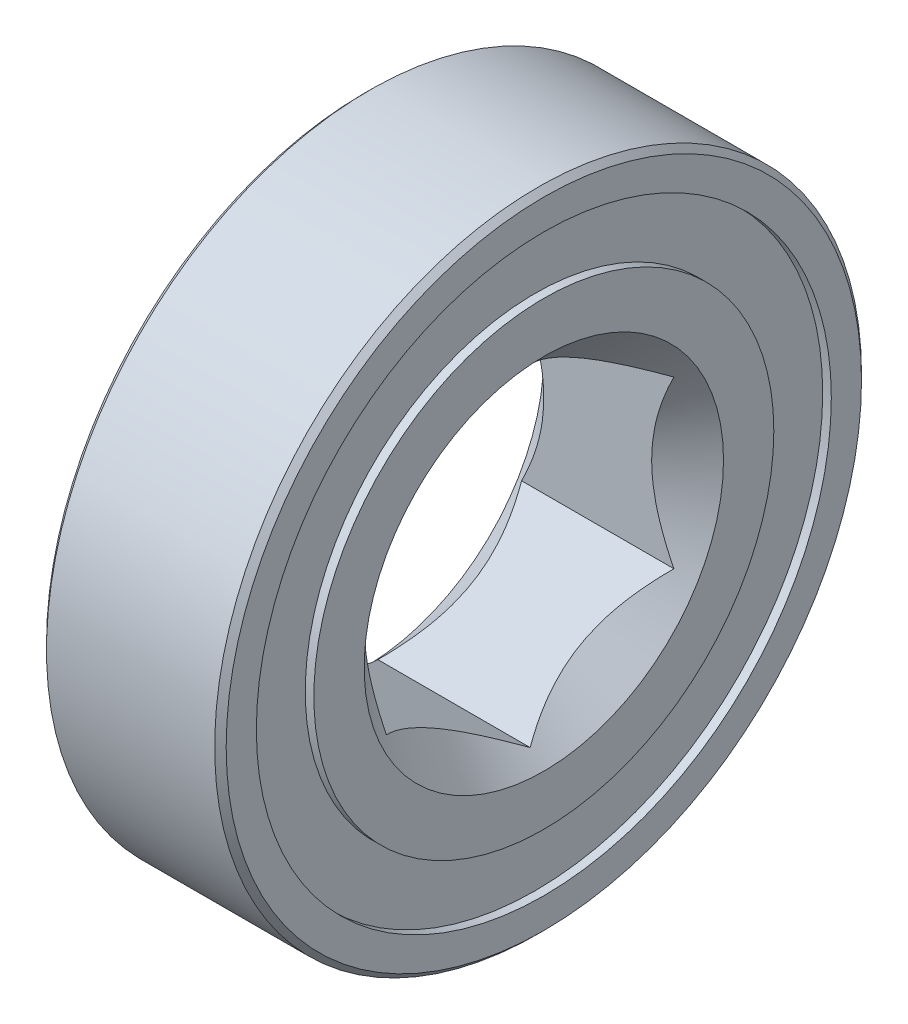
SolidWorks part; units mm, degrees
material "Plain Carbon Steel"
ref_plane "Front" through (0, 0, 0) normal (0, 0, 1) x (1, 0, 0)
ref_plane "Top" through (0, 0, 0) normal (0, 1, 0) x (1, 0, 0)
ref_plane "Right" through (0, 0, 0) normal (1, 0, 0) x (0, 0, -1)
sketch "Sketch1" plane through (0, 0, 0) normal (0, 0, 1) x (1, 0, 0)
  line L0 (0.254, 14.2875) -> (7.6835, 14.2875)
  line L1 (7.9375, 14.0335) -> (7.9375, 12.7)
  line L2 (7.9375, 12.7) -> (7.5565, 12.7)
  line L3 (7.5565, 12.7) -> (7.5565, 10.16)
  line L4 (7.5565, 10.16) -> (7.9375, 10.16)
  line L5 (7.9375, 10.16) -> (7.9375, 7.9375)
  line L6 (7.9375, 7.9375) -> (6.35, 6.35)
  line L7 (6.35, 6.35) -> (1.5875, 6.35)
  line L8 (1.5875, 6.35) -> (0, 7.9375)
  line L9 (0, 7.9375) -> (0, 10.16)
  line L10 (0, 10.16) -> (0.381, 10.16)
  line L11 (0.381, 10.16) -> (0.381, 12.7)
  line L12 (0.381, 12.7) -> (0, 12.7)
  line L13 (0, 12.7) -> (0, 14.0335)
  line L14 (0, 0) -> (-15.8933, 0) construction
  line L15 (0, 14.0335) -> (0.254, 14.2875)
  line L16 (7.6835, 14.2875) -> (7.9375, 14.0335)
  point P1 (7.9375, 14.2875)
  point P2 (0, 0)
  point P15 (0, 14.2875)
  point P18 (7.8534, 13.329)
  dimension "D1" = 12.7
  dimension "D2" = 28.575
  dimension "D3" = 25.4
  dimension "D4" = 20.32
  dimension "D5" = 15.875
  dimension "D6" = 0.381
  dimension "D7" = 7.9375
revolve "Revolve1" add sketch "Sketch1" angle 360 about L14
sketch "Sketch2" plane through (7.9375, 0, 0) normal (1, 0, 0) x (0, 0, -1)
  line L1 (0, 7.3323) -> (-6.35, 3.6662)
  line L2 (-6.35, 3.6662) -> (-6.35, -3.6662)
  line L3 (-6.35, -3.6662) -> (0, -7.3323)
  line L4 (0, -7.3323) -> (6.35, -3.6662)
  line L5 (6.35, -3.6662) -> (6.35, 3.6662)
  line L6 (6.35, 3.6662) -> (0, 7.3323)
  circle A0 centre (0, 0) radius 6.35 construction
  circle A1 centre (0, 0) radius 6.35 construction
extrude "Cut-Extrude1" cut sketch "Sketch2" against normal through all
